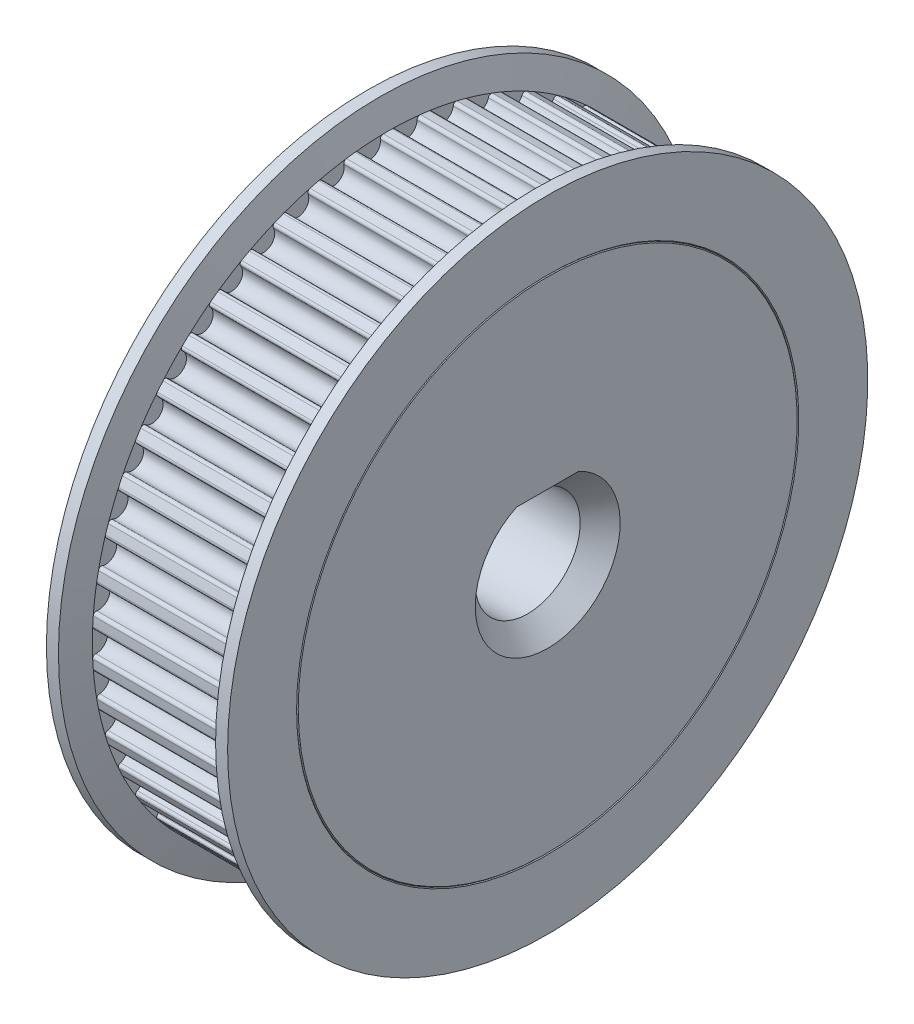
SolidWorks part; units mm, degrees
material "6061-O (SS)"
ref_plane "Сверху" through (0, 0, 0) normal (0, 0, 1) x (1, 0, 0)
ref_plane "Справа" through (0, 0, 0) normal (0, 1, 0) x (1, 0, 0)
ref_plane "Спереди" through (0, 0, 0) normal (1, 0, 0) x (0, 0, -1)
sketch "Эскиз1" plane through (0, 0, 0) normal (0, 0, 1) x (1, 0, 0)
  line L0 (0, 0) -> (0, 7.2824)
  line L1 (0, 7.2824) -> (0.2, 7.5)
  line L2 (0.2, 7.5) -> (6, 7.5)
  line L3 (14.9588, 12.5217) -> (5.3685, 12.5217) construction
  line L4 (7, 14.78) -> (14, 14.78)
  line L5 (6, 7.5) -> (6, 12.4805)
  line L6 (14.3982, 16.0142) -> (15, 16.0142)
  line L7 (15, 0) -> (15, 12.4805)
  line L8 (15, 12.4805) -> (14.9588, 12.5217)
  line L9 (14.9588, 12.5217) -> (15, 12.5629)
  line L10 (15, 12.5629) -> (15, 16.0142)
  line L11 (0, 0) -> (15, 0)
  line L12 (6, 16.0796) -> (6.6018, 16.0796)
  line L13 (14, 14.78) -> (14.3982, 16.0142)
  line L14 (6.6018, 16.0796) -> (7, 14.78)
  line L15 (6, 12.4805) -> (6.0412, 12.5217)
  line L16 (6.0412, 12.5217) -> (6, 12.5629)
  line L17 (6, 12.5629) -> (6, 16.0796)
  dimension "D1" = 1
  dimension "D2" = 5.8
  dimension "D3" = 7.5
  dimension "D4" = 15
  dimension "D5" = 1
  dimension "D6" = 14.78
  dimension "D8" = 7
revolve "Body" add sketch "Эскиз1" angle 360 about L11
sketch "Эскиз2" plane through (15, 0, 0) normal (1, 0, 0) x (0, 0, -1)
  line L0 (-1.3096, 2.275) -> (1.3096, 2.275)
  line L1 (-4.8936, -2.625) -> (6.0252, -2.625) construction
  arc A0 (-1.3096, 2.275) -> (1.3096, 2.275) centre (0, 0) ccw
  dimension "D1" = 5.25
  dimension "D2" = 4.9
extrude "Bore" cut sketch "Эскиз2" against normal through all
sketch "Эскиз3" plane through (6, 0, 0) normal (-1, 0, 0) x (0, 0, 1)
  line L0 (0, 0) -> (9.7637, 0) construction
  circle A0 centre (14.4574, -1.8264) radius 0.55
  circle A1 centre (-11.7892, -8.5654) radius 0.55
  circle A2 centre (14.1144, -3.624) radius 0.55
  circle A3 centre (13.5489, -5.3644) radius 0.55
  circle A4 centre (12.7698, -7.0202) radius 0.55
  circle A5 centre (11.7892, -8.5654) radius 0.55
  circle A6 centre (14.5723, 0) radius 0.55
  circle A7 centre (10.6227, -9.9754) radius 0.55
  circle A8 centre (9.2887, -11.2281) radius 0.55
  circle A9 centre (7.8082, -12.3038) radius 0.55
  circle A10 centre (6.2046, -13.1854) radius 0.55
  circle A11 centre (4.5031, -13.859) radius 0.55
  circle A12 centre (2.7306, -14.3141) radius 0.55
  circle A13 centre (0.915, -14.5435) radius 0.55
  circle A14 centre (-0.915, -14.5435) radius 0.55
  circle A15 centre (-12.7698, -7.0202) radius 0.55
  circle A16 centre (-13.5489, -5.3644) radius 0.55
  circle A17 centre (-2.7306, -14.3141) radius 0.55
  circle A18 centre (-4.5031, -13.859) radius 0.55
  circle A19 centre (-6.2046, -13.1854) radius 0.55
  circle A20 centre (-7.8082, -12.3038) radius 0.55
  circle A21 centre (-9.2887, -11.2281) radius 0.55
  circle A22 centre (-10.6227, -9.9754) radius 0.55
  circle A23 centre (-14.1144, -3.624) radius 0.55
  circle A24 centre (-14.4574, -1.8264) radius 0.55
  circle A25 centre (-14.5723, 0) radius 0.55
  circle A26 centre (-14.4574, 1.8264) radius 0.55
  circle A27 centre (-14.1144, 3.624) radius 0.55
  circle A28 centre (-13.5489, 5.3644) radius 0.55
  circle A29 centre (-12.7698, 7.0202) radius 0.55
  circle A30 centre (-11.7892, 8.5654) radius 0.55
  circle A31 centre (-10.6227, 9.9754) radius 0.55
  circle A32 centre (-9.2887, 11.2281) radius 0.55
  circle A33 centre (-7.8082, 12.3038) radius 0.55
  circle A34 centre (-6.2046, 13.1854) radius 0.55
  circle A35 centre (-4.5031, 13.859) radius 0.55
  circle A36 centre (-2.7306, 14.3141) radius 0.55
  circle A37 centre (-0.915, 14.5435) radius 0.55
  circle A38 centre (0.915, 14.5435) radius 0.55
  circle A39 centre (2.7306, 14.3141) radius 0.55
  circle A40 centre (4.5031, 13.859) radius 0.55
  circle A41 centre (6.2046, 13.1854) radius 0.55
  circle A42 centre (7.8082, 12.3038) radius 0.55
  circle A43 centre (9.2887, 11.2281) radius 0.55
  circle A44 centre (10.6227, 9.9754) radius 0.55
  circle A45 centre (11.7892, 8.5654) radius 0.55
  circle A46 centre (12.7698, 7.0202) radius 0.55
  circle A47 centre (13.5489, 5.3644) radius 0.55
  circle A48 centre (14.1144, 3.624) radius 0.55
  circle A49 centre (14.4574, 1.8264) radius 0.55
  point P45 (0, 0)
  dimension "D1" = 50
  dimension "D2" = 1.83
extrude "20tooth" cut sketch "Эскиз3" against normal blind 7 from offset 1 offset against normal yes
fillet "Скругление1" radius 0.15 100 edges at (10.5, 0.5128, 14.7711) (10.5, -0.5128, 14.7711) (10.5, -1.3426, 14.7189) (10.5, -2.3601, 14.5904) (10.5, -3.1767, 14.4346) (10.5, -4.1701, 14.1795) (10.5, -4.9608, 13.9226) (10.5, -5.9144, 13.545) (10.5, -6.6667, 13.1911) (10.5, -7.5654, 12.697) (10.5, -8.2674, 12.2515) (10.5, -9.0971, 11.6487) (10.5, -9.7377, 11.1187) (10.5, -10.4853, 10.4166) (10.5, -11.0545, 9.8106) (10.5, -11.7082, 9.0203) (10.5, -12.1969, 8.3477) (10.5, -12.7464, 7.4818) (10.5, -13.147, 6.7532) (10.5, -13.5836, 5.8252) (10.5, -13.8897, 5.0522) (10.5, -14.2066, 4.0768) (10.5, -14.4134, 3.2715) (10.5, -14.6056, 2.2641) (10.5, -14.7098, 1.4393) (10.5, -14.7742, 0.4157) (10.5, -14.7742, -0.4157) (10.5, -14.7098, -1.4393) (10.5, -14.6056, -2.2641) (10.5, -14.4134, -3.2715) (10.5, -14.2066, -4.0768) (10.5, -13.8897, -5.0522) (10.5, -13.5836, -5.8252) (10.5, -13.147, -6.7532) (10.5, -12.7464, -7.4818) (10.5, -12.1969, -8.3477) (10.5, -11.7082, -9.0203) (10.5, -11.0545, -9.8106) (10.5, -10.4853, -10.4166) (10.5, -9.7377, -11.1187) (10.5, -4.1701, -14.1795) (10.5, -3.1767, -14.4346) (10.5, -5.9144, -13.545) (10.5, -4.9608, -13.9226) (10.5, -7.5654, -12.697) (10.5, -6.6667, -13.1911) (10.5, -9.0971, -11.6487) (10.5, -8.2674, -12.2515) (10.5, -2.3601, -14.5904) (10.5, -1.3426, -14.7189) (10.5, -0.5128, -14.7711) (10.5, 0.5128, -14.7711) (10.5, 1.3426, -14.7189) (10.5, 2.3601, -14.5904) (10.5, 3.1767, -14.4346) (10.5, 4.1701, -14.1795) (10.5, 4.9608, -13.9226) (10.5, 5.9144, -13.545) (10.5, 6.6667, -13.1911) (10.5, 7.5654, -12.697) (10.5, 8.2674, -12.2515) (10.5, 9.0971, -11.6487) (10.5, 9.7377, -11.1187) (10.5, 10.4853, -10.4166) (10.5, 11.0545, -9.8106) (10.5, 11.7082, -9.0203) (10.5, 12.1969, -8.3477) (10.5, 12.7464, -7.4818) (10.5, 13.147, -6.7532) (10.5, 13.5836, -5.8252) (10.5, 13.8897, -5.0522) (10.5, 14.2066, -4.0768) (10.5, 14.4134, -3.2715) (10.5, 14.6056, -2.2641) (10.5, 14.7098, -1.4393) (10.5, 14.7742, -0.4157) (10.5, 14.7742, 0.4157) (10.5, 14.7098, 1.4393) (10.5, 14.6056, 2.2641) (10.5, 14.4134, 3.2715) (10.5, 14.2066, 4.0768) (10.5, 13.8897, 5.0522) (10.5, 13.5836, 5.8252) (10.5, 13.147, 6.7532) (10.5, 12.7464, 7.4818) (10.5, 12.1969, 8.3477) (10.5, 11.7082, 9.0203) (10.5, 11.0545, 9.8106) (10.5, 10.4853, 10.4166) (10.5, 9.7377, 11.1187) (10.5, 9.0971, 11.6487) (10.5, 8.2674, 12.2515) (10.5, 7.5654, 12.697) (10.5, 6.6667, 13.1911) (10.5, 5.9144, 13.545) (10.5, 4.9608, 13.9226) (10.5, 4.1701, 14.1795) (10.5, 3.1767, 14.4346) (10.5, 2.3601, 14.5904) (10.5, 1.3426, 14.7189)
chamfer "Chamfer4" distance 1 angle 45 2 edges at (0, -2.625, 0) (0, 2.275, 0)
chamfer "Chamfer5" distance 1 angle 45 2 edges at (15, -2.625, 0) (15, 2.275, 0)
